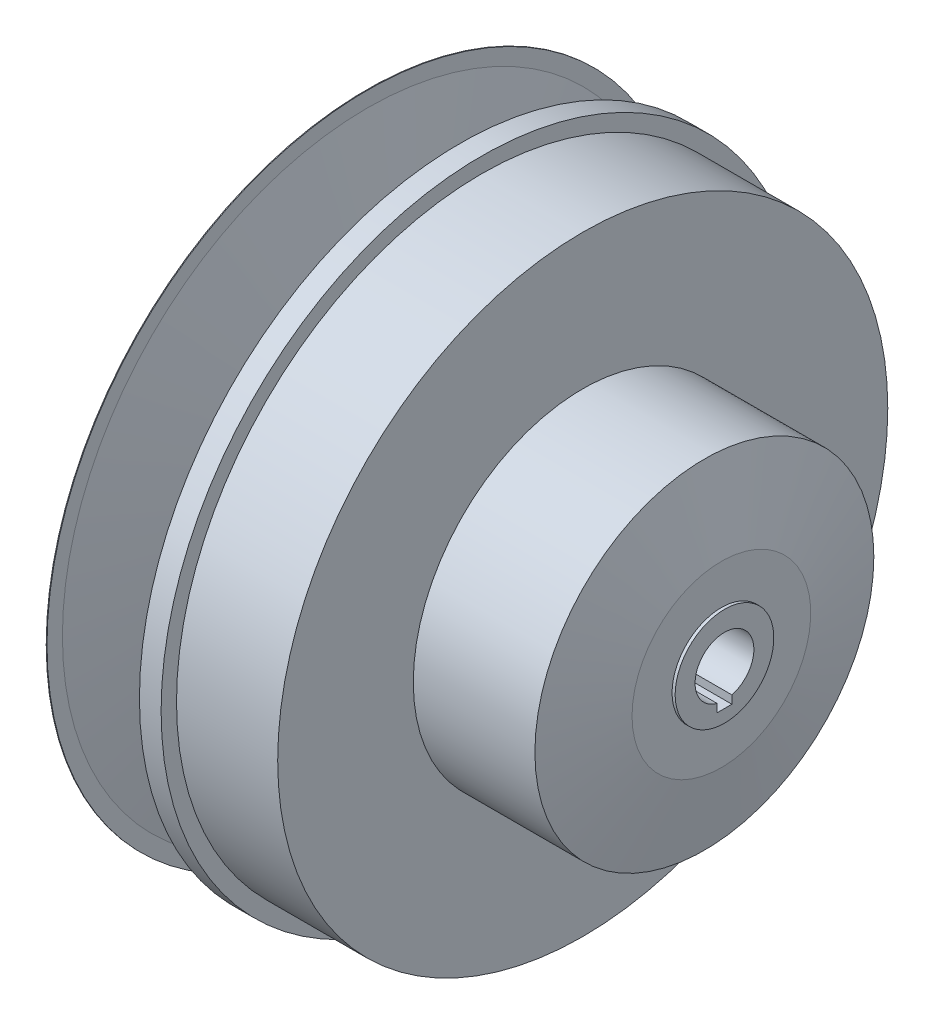
SolidWorks part; units mm, degrees
ref_plane "Front Plane" through (0, 0, 0) normal (0, 0, 1) x (1, 0, 0)
ref_plane "Top Plane" through (0, 0, 0) normal (0, 1, 0) x (1, 0, 0)
ref_plane "Right Plane" through (0, 0, 0) normal (1, 0, 0) x (0, 0, -1)
sketch "Sketch1" plane through (0, 0, 0) normal (0, 0, 1) x (1, 0, 0)
  line L0 (-178.7954, 0) -> (158.9063, 0) construction
  line L1 (-162.9901, 0) -> (-162.9901, 16.125)
  line L2 (-162.9901, 16.125) -> (-163.9901, 16.125)
  line L3 (-163.9901, 16.125) -> (-163.9901, 37.7415)
  line L4 (-163.9901, 37.7415) -> (-160.1231, 37.7415)
  line L5 (-160.1231, 37.7415) -> (-160.1231, 99)
  line L6 (-159.0636, 104) -> (-159.3136, 104)
  line L7 (-159.0636, 99) -> (-148.3524, 37.19)
  line L8 (-148.3524, 37.19) -> (-148.3524, 29.19)
  line L9 (-148.3524, 29.19) -> (-145.0112, 29.19)
  line L10 (-145.0112, 29.19) -> (-145.0112, 37.19)
  line L11 (-145.0112, 37.19) -> (-129.0636, 104)
  line L12 (-129.0636, 104) -> (-122.0281, 104)
  line L13 (-122.0281, 104) -> (-122.0281, 99)
  line L14 (-122.0281, 99) -> (-89.1901, 99)
  line L15 (-89.1901, 99) -> (-89.1901, 55)
  line L16 (-89.1901, 55) -> (-49.7166, 55)
  line L17 (-159.0636, 99) -> (-159.0636, 104)
  line L18 (-159.3136, 104) -> (-159.3136, 99)
  line L19 (-159.3136, 99) -> (-160.1231, 99)
  line L20 (-44.1901, 29) -> (-44.1901, 16.0152)
  line L21 (-44.1901, 16.0152) -> (-43.1901, 16.0152)
  line L22 (-43.1901, 16.0152) -> (-43.1901, 0)
  line L23 (-49.7166, 55) -> (-44.1901, 29)
  line L24 (-162.9901, 0) -> (-43.1901, 0)
  point P20 (-44.1901, 55)
  dimension "D1" = 16.125
  dimension "D2" = 1
  dimension "D3" = 3.867
  dimension "D4" = 99
  dimension "D5" = 5
  dimension "D6" = 32.838
  dimension "D7" = 44
  dimension "D8" = 45
  dimension "D9" = 0.25
  dimension "D10" = 8
  dimension "D11" = 1
  dimension "D12" = 26
  dimension "D13" = 12
  dimension "D14" = 30
  dimension "D15" = 119.8
revolve "Revolve1" add sketch "Sketch1" angle 360 about L24
sketch "Sketch2" plane through (-162.9901, 0, 0) normal (-1, 0, 0) x (0, 0, 1)
  circle A0 centre (0, 0) radius 15.125
  dimension "D1" = 30.25
extrude "Cut-Extrude5" cut sketch "Sketch2" against normal blind 24.4 contours A0
sketch "Sketch3" plane through (-138.5901, 0, 0) normal (-1, 0, 0) x (0, 0, 1)
  circle A0 centre (0, 0) radius 9.543
  dimension "D1" = 19.086
extrude "Cut-Extrude6" cut sketch "Sketch3" against normal up to next
sketch "Sketch4" plane through (-43.1901, 0, 0) normal (1, 0, 0) x (0, 0, -1)
  line L1 (-2.4, -7.219) -> (2.4, -7.219)
  line L2 (-2.4, -7.219) -> (-2.4, -11.867)
  line L3 (-2.4, -11.867) -> (2.4, -11.867)
  line L4 (2.4, -7.219) -> (2.4, -11.867)
  dimension "D2" = 4.8
extrude "Cut-Extrude7" cut sketch "Sketch4" against normal up to next
